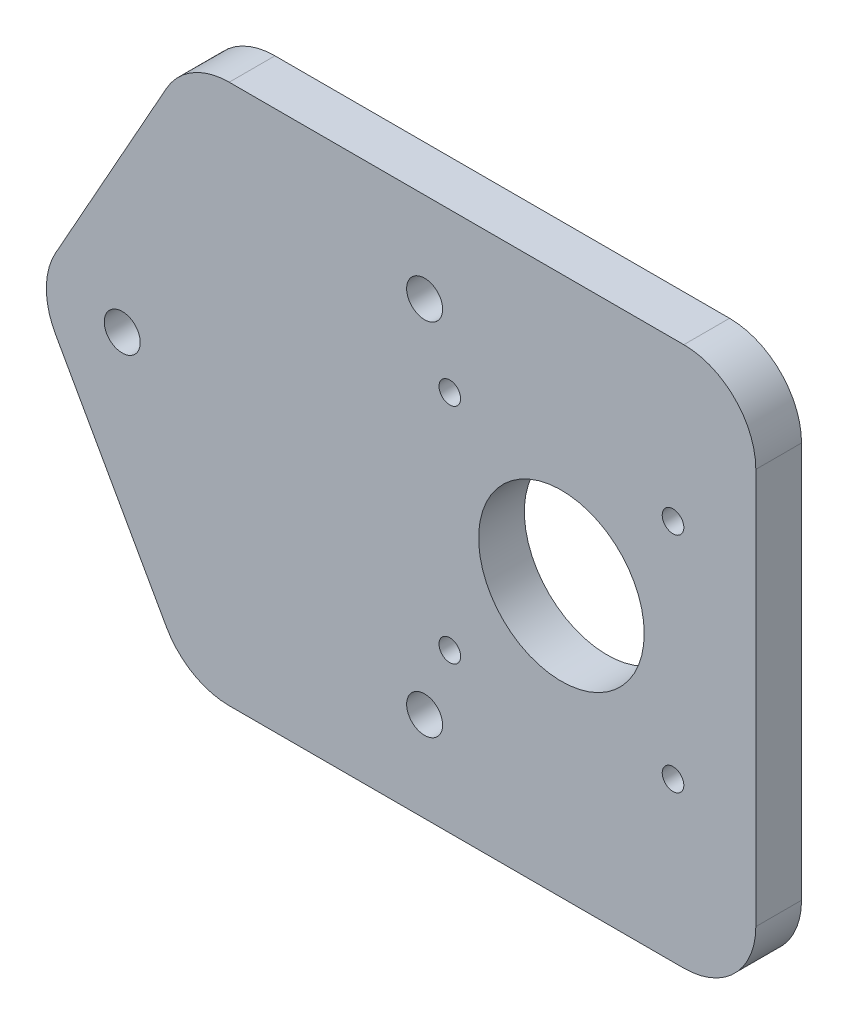
SolidWorks part; units mm, degrees
ref_plane "Front Plane" through (0, 0, 0) normal (0, 0, 1) x (1, 0, 0)
ref_plane "Top Plane" through (0, 0, 0) normal (0, 1, 0) x (1, 0, 0)
ref_plane "Right Plane" through (0, 0, 0) normal (1, 0, 0) x (0, 0, -1)
sketch "Sketch1" plane through (0, 0, 0) normal (0, 0, 1) x (1, 0, 0)
  line L1 (0, 0) -> (100, 0)
  line L2 (0, 0) -> (0, 75)
  line L3 (0, 75) -> (100, 75)
  line L4 (100, 0) -> (100, 75)
  dimension "D1" = 75
  dimension "D2" = 100
extrude "plate" add sketch "Sketch1" along normal blind 6.35
sketch "Sketch2" plane through (0, 0, 6.35) normal (0, 0, 1) x (1, 0, 0)
  line L0 (12, 75) -> (12, 0) construction
  line L1 (100, 75) -> (0, 75) construction
  line L2 (0, 0) -> (100, 0) construction
  line L3 (54, 75) -> (54, 0) construction
  line L4 (17, 75) -> (17, 0) construction
  line L5 (49, 75) -> (49, 0) construction
  line L6 (0, 75) -> (0, 0) construction
  line L7 (33, 75) -> (33, 0) construction
  line L8 (17, 0) -> (49, 75) construction
  circle A3 centre (54, 62.5) radius 2.5
  circle A4 centre (12, 37.5) radius 2.5
  circle A5 centre (54, 12.5) radius 2.5
  point P20 (12, 37.5)
  point P23 (33, 37.5)
  dimension "D1" = 5
  dimension "D2" = 5
  dimension "D3" = 32
  dimension "D4" = 12
extrude "cut idler holes" cut sketch "Sketch2" against normal through all
sketch "Sketch3" plane through (0, 0, 6.35) normal (0, 0, 1) x (1, 0, 0)
  line L0 (0, 37.5) -> (100, 37.5) construction
  line L1 (57.5, 22) -> (88.5, 22) construction
  line L2 (57.5, 22) -> (57.5, 53) construction
  line L3 (57.5, 53) -> (88.5, 53) construction
  line L4 (88.5, 22) -> (88.5, 53) construction
  line L5 (57.5, 22) -> (88.5, 53) construction
  line L6 (57.5, 53) -> (88.5, 22) construction
  line L7 (0, 75) -> (0, 0) construction
  line L8 (100, 0) -> (100, 75) construction
  line L9 (33, 75) -> (33, 0) construction
  circle A0 centre (57.5, 53) radius 1.5
  circle A1 centre (88.5, 53) radius 1.5
  circle A2 centre (88.5, 22) radius 1.5
  circle A3 centre (57.5, 22) radius 1.5
  circle A4 centre (73, 37.5) radius 11.5
  point P0 (73, 37.5)
  dimension "D1" = 3
  dimension "D2" = 23
  dimension "D3" = 31
  dimension "D4" = 40
extrude "cut motor holes" cut sketch "Sketch3" against normal through all
ref_plane "Plane1" through (33, 0, 0) normal (1, 0, 0) x (0, 0, -1)
chamfer "Chamfer1" distance 1.5 angle 45 4 edges at (90, 22, 0) (59, 22, 0) (90, 53, 0) (59, 53, 0)
fillet "Fillet1" radius 10 4 edges at (0, 75, 3.175) (100, 0, 3.175) (0, 0, 3.175) (100, 75, 3.175)
ref_plane "Plane2" through (0, 37.5, 0) normal (0, -1, 0) x (-1, 0, 0)
sketch "Sketch4" plane through (0, 0, 6.35) normal (0, 0, 1) x (1, 0, 0)
  line L2 (90, 75) -> (10, 75) construction
  line L3 (10, 0) -> (90, 0) construction
  line L5 (21, 0) -> (21, 75) construction
  line L8 (0, 65) -> (0, 10) construction
  line L10 (21, 0) -> (10, 0)
  line L15 (21, 75) -> (10, 75)
  line L16 (21, 0) -> (0, 37.5)
  line L17 (21, 75) -> (0, 37.5)
  line L18 (0, 65) -> (0, 37.5)
  line L19 (0, 37.5) -> (0, 10)
  arc A0 (0, 10) -> (10, 0) centre (10, 10) ccw
  arc A3 (10, 75) -> (0, 65) centre (10, 65) ccw
  dimension "D1" = 21
extrude "Cut-Extrude1" cut sketch "Sketch4" against normal up to surface (6.35 mm away)
mirror "Mirror2" about plane through (0, 37.5, 0) normal (0, -1, 0) of "Cut-Extrude1"
fillet "Fillet5" radius 10 3 edges at (21, 0, 3.175) (0, 37.5, 3.175) (21, 75, 3.175)
